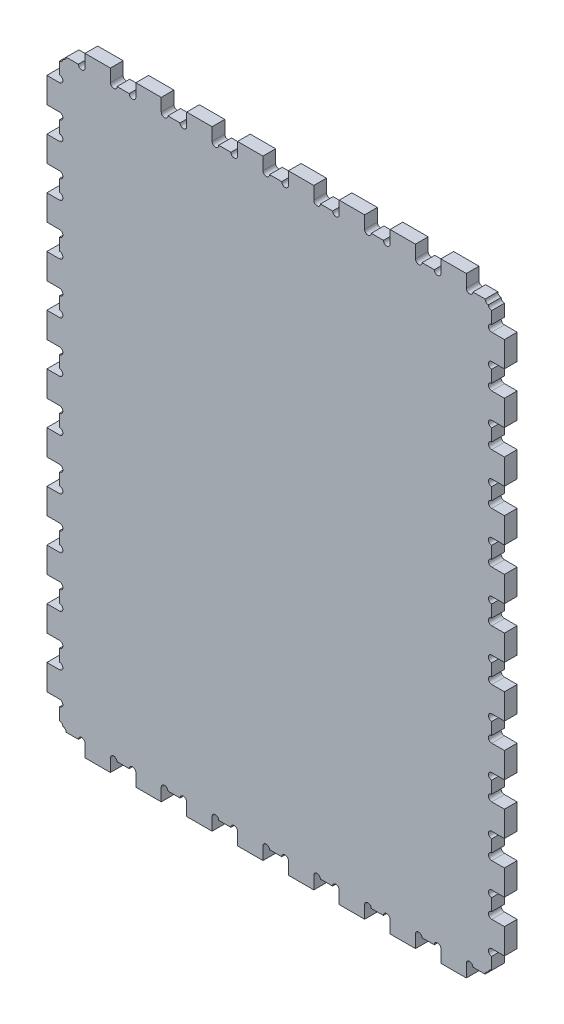
SolidWorks part; units mm, degrees
ref_plane "Front Plane" through (0, 0, 0) normal (0, 0, 1) x (1, 0, 0)
ref_plane "Top Plane" through (0, 0, 0) normal (0, 1, 0) x (1, 0, 0)
ref_plane "Right Plane" through (0, 0, 0) normal (1, 0, 0) x (0, 0, -1)
sketch "Sketch1" plane through (0, 0, 0) normal (0, 0, 1) x (1, 0, 0)
  line L1 (228.6, -304.8) -> (-228.6, -304.8)
  line L2 (228.6, -304.8) -> (228.6, 304.8)
  line L3 (228.6, 304.8) -> (-228.6, 304.8)
  line L4 (-228.6, -304.8) -> (-228.6, 304.8)
  line L5 (228.6, -304.8) -> (-228.6, 304.8) construction
  line L6 (228.6, 304.8) -> (-228.6, -304.8) construction
  line L9 (-203.2, 304.8) -> (-228.6, 304.8) construction
  point P0 (0, 0)
  point P7 (0, 0)
  dimension "D1" = 457.2
  dimension "D2" = 609.6
extrude "Boss-Extrude1" add sketch "Sketch1" along normal blind 12.7
sketch "Sketch2" plane through (0, 0, 12.7) normal (0, 0, 1) x (1, 0, 0)
  line L0 (228.6, 304.8) -> (-228.6, 304.8) construction
  line L1 (-215.9, 292.1) -> (-228.6, 292.1) construction
  line L2 (-215.9, 304.8) -> (-190.5, 304.8)
  line L3 (-215.9, 304.8) -> (-215.9, 292.1)
  line L4 (-215.9, 292.1) -> (-190.5, 292.1)
  line L5 (-190.5, 304.8) -> (-190.5, 292.1)
  line L6 (-228.6, 304.8) -> (-228.6, -304.8) construction
  circle A0 centre (-212.598, 292.1) radius 3.302
  circle A1 centre (-193.802, 292.1) radius 3.302
  point P13 (-200.025, 292.1)
  point P14 (-200.025, 292.1)
  line M10 (228.6, 304.8) -> (-228.6, 304.8)
  dimension "D4" = 6.604
  dimension "D5" = 6.604
  dimension "D1" = 25.4
  dimension "D2" = 12.7
  dimension "D3" = 12.7
extrude "Cut-Extrude1" cut sketch "Sketch2" against normal through all contours A1 L5 L3 A0 L4 M10 | L4 A0 | L4 A0 | L4 A1 | L4 A1
pattern_linear "LPattern1" count 9 spacing 50.8 along (1, 0, 0) of "Cut-Extrude1"
sketch "Sketch6" plane through (0, 0, 12.7) normal (0, 0, 1) x (1, 0, 0)
  line L1 (-228.6, 304.8) -> (-215.9, 304.8)
  line L2 (-228.6, 304.8) -> (-228.6, 292.1)
  line L3 (-228.6, 292.1) -> (-215.9, 292.1)
  line L4 (-215.9, 304.8) -> (-215.9, 292.1)
extrude "Cut-Extrude4" cut sketch "Sketch6" against normal through all
sketch "Sketch3" plane through (0, 0, 12.7) normal (0, 0, 1) x (1, 0, 0)
  line L0 (-228.6, 292.1) -> (-228.6, -304.8) construction
  line L1 (-228.6, 292.1) -> (-215.9, 292.1)
  line L2 (-228.6, 292.1) -> (-228.6, 266.7)
  line L3 (-228.6, 266.7) -> (-215.9, 266.7)
  line L4 (-215.9, 292.1) -> (-215.9, 266.7)
  line L5 (-215.9, 292.1) -> (-182.9158, 292.1) construction
  line L6 (-182.9158, 292.1) -> (-182.9158, 304.8) construction
  line L8 (-165.1, 304.8) -> (-190.5, 304.8) construction
  circle A0 centre (-215.9, 288.798) radius 3.302
  circle A1 centre (-215.9, 270.002) radius 3.302
  dimension "D3" = 6.604
  dimension "D4" = 6.604
  dimension "D1" = 25.4
  dimension "D2" = 12.7
  dimension "D5" = 12.7
extrude "Cut-Extrude2" cut sketch "Sketch3" against normal through all contours A1 L4 A0 L1 L2 L3 | L4 A0 | L4 A0 | L4 A1 | L4 A1
pattern_linear "LPattern2" count 12 spacing 50.8 along (0, -1, 0) of "Cut-Extrude2"
ref_plane "Plane1" through (0, 0, 0) normal (1, 0, 0) x (0, 0, -1)
ref_plane "Plane2" through (0, 0, 0) normal (0, 1, 0) x (1, 0, 0)
mirror "Mirror6" about plane through (0, 0, 0) normal (1, 0, 0) of "Cut-Extrude4"
mirror "Mirror7" about plane through (0, 0, 0) normal (0, 1, 0) of "Mirror6", "Cut-Extrude4"
mirror "Mirror1" about plane through (0, 0, 0) normal (1, 0, 0) of "LPattern2", "Cut-Extrude2"
mirror "Mirror2" about plane through (0, 0, 0) normal (0, 1, 0) of "LPattern1", "Cut-Extrude1"
sketch "Sketch5" plane through (0, 0, 12.7) normal (0, 0, 1) x (1, 0, 0)
  line L1 (-228.6, 304.8) -> (-190.5, 304.8)
  line L2 (-228.6, 304.8) -> (-228.6, 292.1)
  line L3 (-228.6, 292.1) -> (-190.5, 292.1)
  line L4 (-190.5, 304.8) -> (-190.5, 292.1)
  line L5 (-228.6, 304.8) -> (-215.9, 304.8)
  line L6 (-228.6, 304.8) -> (-228.6, 266.7)
  line L7 (-228.6, 266.7) -> (-215.9, 266.7)
  line L8 (-215.9, 304.8) -> (-215.9, 266.7)
  arc A0 (-190.5, 292.1) -> (-183.896, 292.1) centre (-187.198, 292.1) ccw construction
extrude "Cut-Extrude3" cut sketch "Sketch5" against normal through all contours L1 L8 L3 L4 | L8 L3 L6 L7 | L8 L1 L2 L3
mirror "Mirror3" about plane through (0, 0, 0) normal (1, 0, 0)
mirror "Mirror4" about plane through (0, 0, 0) normal (0, 1, 0)
mirror "Mirror5" about plane through (0, 0, 0) normal (0, 1, 0)
